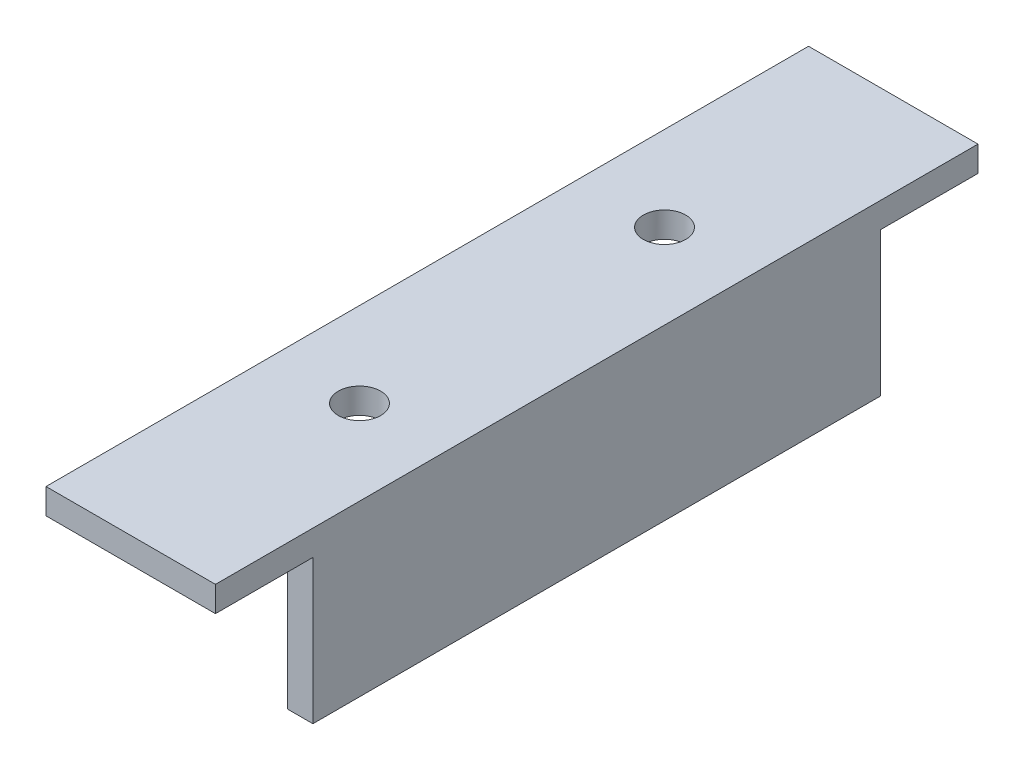
SolidWorks part; units mm, degrees
ref_plane "Front Plane" through (0, 0, 0) normal (0, 0, 1) x (1, 0, 0)
ref_plane "Top Plane" through (0, 0, 0) normal (0, 1, 0) x (1, 0, 0)
ref_plane "Right Plane" through (0, 0, 0) normal (1, 0, 0) x (0, 0, -1)
sketch "Sketch1" plane through (0, 0, 0) normal (0, 0, 1) x (1, 0, 0)
  line L0 (0, 0) -> (40, 0)
  line L1 (40, 0) -> (40, -40)
  line L2 (0, -6) -> (34, -6)
  line L3 (34, -6) -> (34, -40)
  line L4 (0, -6) -> (0, 0)
  line L5 (34, -40) -> (40, -40)
  dimension "D1" = 40
  dimension "D2" = 40
  dimension "D4" = 6
  dimension "D3" = 6
extrude "Boss-Extrude1" add sketch "Sketch1" against normal blind 180
sketch "Sketch2" plane through (34, 0, 0) normal (-1, 0, 0) x (0, 0, 1)
  line L0 (-180, -40) -> (0, -40) construction
  line L1 (0, -6) -> (-23, -6)
  line L2 (0, -6) -> (0, -40)
  line L3 (0, -40) -> (-23, -40)
  line L4 (-23, -6) -> (-23, -40)
  line L6 (-180, -6) -> (-157, -6)
  line L7 (-180, -6) -> (-180, -40)
  line L8 (-180, -40) -> (-157, -40)
  line L9 (-157, -6) -> (-157, -40)
  dimension "D1" = 23
  dimension "D2" = 23
extrude "Cut-Extrude1" cut sketch "Sketch2" against normal blind 200
sketch "Sketch3" plane through (0, 0, 0) normal (0, 1, 0) x (1, 0, 0)
  line L0 (0, 180) -> (0, 0) construction
  line L1 (40, 180) -> (0, 180) construction
  line L2 (0, 90) -> (23.6962, 90) construction
  line L3 (40, 0) -> (0, 0) construction
  circle A0 centre (20, 126) radius 5
  circle A1 centre (20, 54) radius 5
  dimension "D3" = 10
  dimension "D1" = 20
  dimension "D2" = 54
  dimension "D4" = 54
  dimension "D5" = 20
extrude "Cut-Extrude2" cut sketch "Sketch3" against normal blind 200
